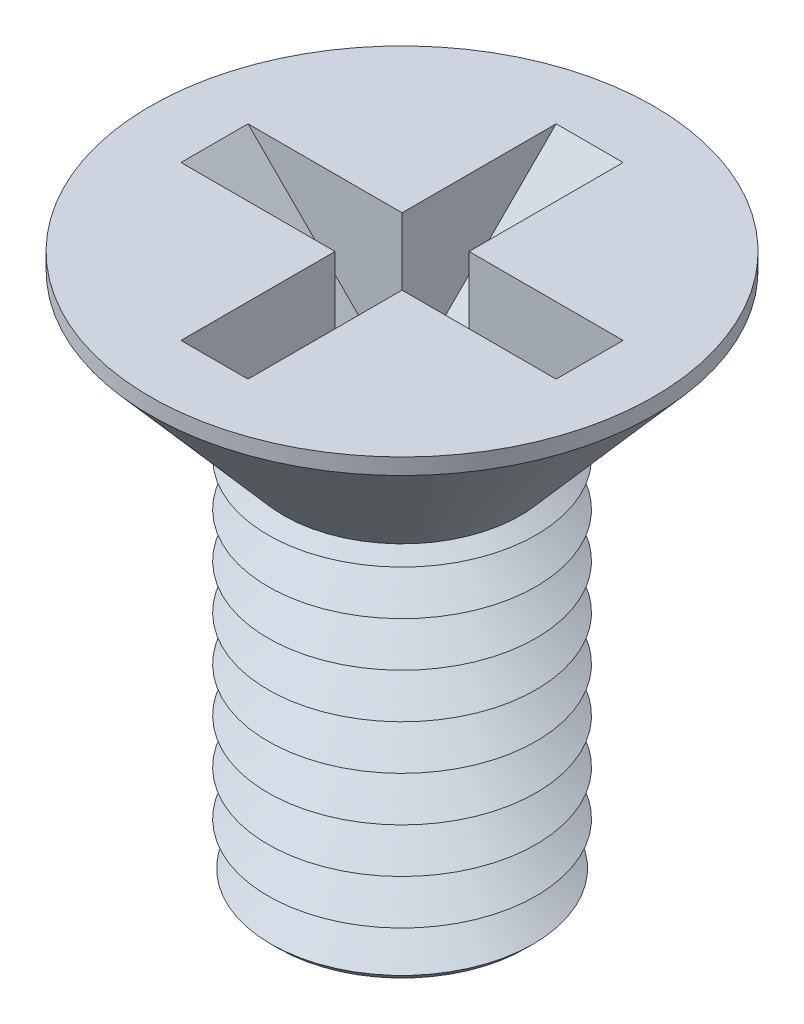
SolidWorks part; units mm, degrees
ref_plane "Front" through (0, 0, 0) normal (0, 0, 1) x (1, 0, 0)
ref_plane "Top" through (0, 0, 0) normal (0, 1, 0) x (1, 0, 0)
ref_plane "Right" through (0, 0, 0) normal (1, 0, 0) x (0, 0, -1)
ref_axis "Axis1" through (0, -50, 0) along (0, 1, 0)
sketch "Sketch ( driver )" plane through (0, 0, 0) normal (0, 0, 1) x (1, 0, 0)
  line L0 (0, 0) -> (1.4318, 0)
  line L1 (1.4318, -0.0914) -> (1.4318, 0)
  line L2 (1.4318, -0.0914) -> (0.762, -0.862)
  line L4 (0.762, -0.862) -> (0.762, -3.0226)
  line L5 (0.762, -3.0226) -> (0.6096, -3.175)
  line L6 (0.6096, -3.175) -> (0, -3.175)
  line L7 (0, -3.175) -> (0, 0)
  line L8 (0, 11.279) -> (0, 0) construction
  line L9 (0.762, 0.762) -> (0.762, 0.508) construction
  line L10 (0.762, 0.508) -> (0.542, 0.635) construction
  line L11 (0.542, 0.635) -> (0.762, 0.762) construction
  circle A0 centre (0, 0) radius 0.1905 construction
  circle A1 centre (0, -0.8763) radius 0.1905 construction
  point P2 (0, -1.0668)
  point P12 (0.1905, 0)
  point P15 (1.5113, 0)
  point P17 (-0.1905, 0)
  dimension "D2" = 45
  dimension "D6" = 41
  dimension "D7" = 3.175
sketch "Sketch3" plane through (0, 0, 0) normal (0, 0, 1) x (1, 0, 0)
  line L8 (0, 0) -> (0, -3.175)
  line L9 (0, -3.175) -> (0.6096, -3.175)
  line L10 (0.6096, -3.175) -> (0.762, -3.0226)
  line L11 (0.762, -3.0226) -> (0.762, 0)
  line L12 (0.762, 0) -> (0, 0)
revolve "Shank Revolve ( driven )" add sketch "Sketch3" angle 360 about axis through (0, -50, 0) along (0, 1, 0)
sketch "Sketch4" plane through (0, 0, 0) normal (0, 0, 1) x (1, 0, 0)
  line L0 (0.542, 0.635) -> (0.762, 0.762)
  line L1 (0.762, 0.762) -> (1.27, 0.762)
  line L2 (1.27, 0.762) -> (1.27, -3.81)
  line L3 (0.542, 0.635) -> (0.762, 0.508)
  line L4 (0.762, 0.508) -> (0.542, 0.381)
  line L5 (0.542, 0.381) -> (0.762, 0.254)
  line L6 (0.762, -0.862) -> (0.762, -3.0226) construction
  line L7 (0.762, 0.254) -> (0.542, 0.127)
  line L8 (0.542, 0.127) -> (0.762, 0)
  line L9 (0.762, 0) -> (0.542, -0.127)
  line L10 (0.542, -0.127) -> (0.762, -0.254)
  line L11 (0.762, -0.254) -> (0.542, -0.381)
  line L12 (0.542, -0.381) -> (0.762, -0.508)
  line L13 (0.762, -0.508) -> (0.542, -0.635)
  line L14 (0.542, -0.635) -> (0.762, -0.762)
  line L15 (0.762, -0.762) -> (0.542, -0.889)
  line L16 (0.542, -0.889) -> (0.762, -1.016)
  line L17 (0.762, -1.016) -> (0.542, -1.143)
  line L18 (0.542, -1.143) -> (0.762, -1.27)
  line L19 (0.762, -1.27) -> (0.542, -1.397)
  line L20 (0.542, -1.397) -> (0.762, -1.524)
  line L21 (0.762, -1.524) -> (0.542, -1.651)
  line L22 (0.542, -1.651) -> (0.762, -1.778)
  line L23 (0.762, -1.778) -> (0.542, -1.905)
  line L24 (0.542, -1.905) -> (0.762, -2.032)
  line L25 (0.762, -2.032) -> (0.542, -2.159)
  line L26 (0.542, -2.159) -> (0.762, -2.286)
  line L27 (0.762, -2.286) -> (0.542, -2.413)
  line L28 (0.542, -2.413) -> (0.762, -2.54)
  line L29 (0.762, -2.54) -> (0.542, -2.667)
  line L30 (0.542, -2.667) -> (0.762, -2.794)
  line L31 (0.762, -2.794) -> (0.542, -2.921)
  line L32 (0.542, -2.921) -> (0.762, -3.048)
  line L33 (0.762, -3.048) -> (0.542, -3.175)
  line L34 (0.542, -3.175) -> (0.762, -3.302)
  line L35 (0.762, -3.302) -> (0.542, -3.429)
  line L36 (0.542, -3.429) -> (0.762, -3.556)
  line L37 (0.762, -3.556) -> (0.542, -3.683)
  line L38 (0.542, -3.683) -> (0.762, -3.81)
  line L39 (0.762, -3.81) -> (1.27, -3.81)
  dimension "D1" = 0.508
revolve "Thread Revolve Cut ( driven )" cut sketch "Sketch4" angle 360 about axis through (0, -50, 0) along (0, 1, 0)
sketch "Sketch5" plane through (0, 0, 0) normal (0, 0, 1) x (1, 0, 0)
  line L2 (0, 0) -> (1.4318, 0)
  line L3 (1.4318, 0) -> (1.4318, -0.0914)
  line L4 (1.4318, -0.0914) -> (0, -1.7386)
  line L5 (0, -1.7386) -> (0, 0)
revolve "Head Revolve ( driven )" add sketch "Sketch5" angle 360 about axis through (0, -50, 0) along (0, 1, 0)
sketch "Sketch7" plane through (0, 0, 0) normal (1, 0, 0) x (0, 0, -1)
  line L0 (0, 0.508) -> (1.5748, 0.508)
  line L1 (1.5748, 0.508) -> (0.1905, -0.8763)
  line L2 (0.1905, -0.8763) -> (0, -0.8763)
  line L3 (0, -0.8763) -> (0, 0.508)
  line L5 (0, 11.279) -> (0, 0) construction
  dimension "D1" = 45
  dimension "D2" = 0.508
extrude "Cut-Extrude1" cut sketch "Sketch7" against normal up to vertex (0.1905 mm away) and the other way up to vertex (0.1905 mm away) up to point (-0.1905, 0, 0) other way up to point (0.1905, 0, 0)
pattern_circular "CirPattern1" count 4 over 360 about axis through (0, 0, 0) along (0, 1, 0) of "Cut-Extrude1"
equation "\"D1@Sketch ( driver )\" = .06 * \"Diam@Sketch ( driver )\""
equation "\"Pitch@Sketch ( driver )\" =  \"Diam@Sketch ( driver )\"/6"
equation "\"D4@Sketch ( driver )\" = .7*\"Diam@Sketch ( driver )\""
equation "\"End Chamfer@Sketch ( driver )\" = .1*\"Diam@Sketch ( driver )\""
equation "\"D5@Sketch ( driver )\" = .25 * \"Diam@Sketch ( driver )\""
equation "\"Threaded@Sketch ( driver )\" = 2.5*\"Diam@Sketch ( driver )\""
